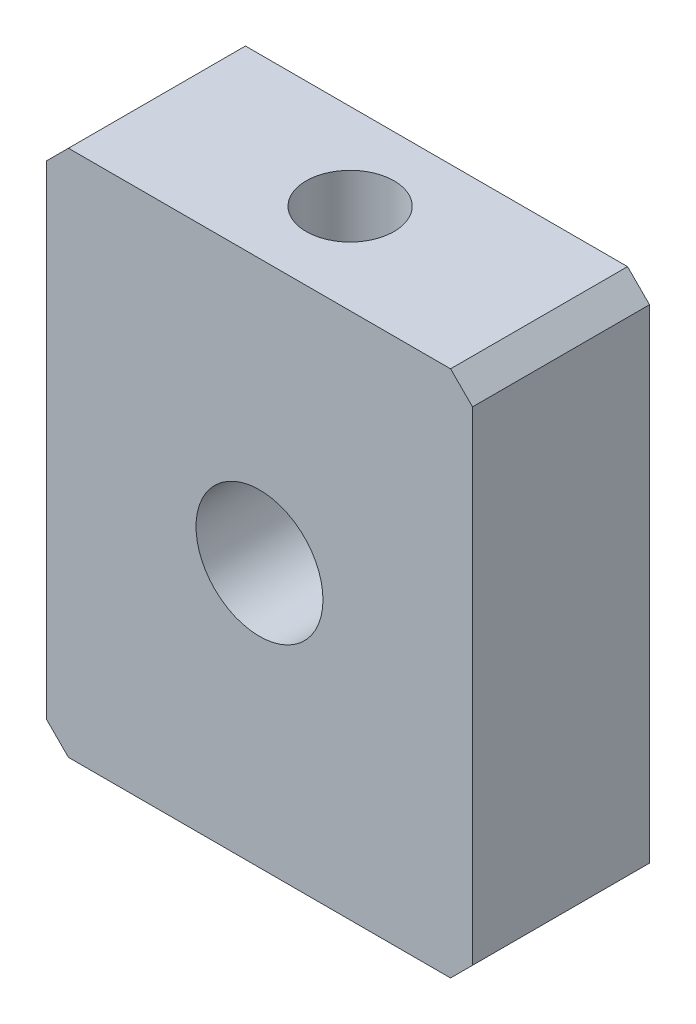
SolidWorks part; units mm, degrees
ref_plane "前视基准面" through (0, 0, 0) normal (0, 0, 1) x (1, 0, 0)
ref_plane "上视基准面" through (0, 0, 0) normal (0, 1, 0) x (1, 0, 0)
ref_plane "右视基准面" through (0, 0, 0) normal (1, 0, 0) x (0, 0, -1)
other "Configuration Table"
sketch "草图1" plane through (0, 0, 52.0651) normal (0, 0, 1) x (1, 0, 0)
  line L0 (-369.3491, 311.962) -> (-369.3491, 664.552) construction
  line L1 (-466.2591, 311.962) -> (-369.3491, 311.962)
  line L2 (-466.2591, 311.962) -> (-466.2591, 431.962)
  line L3 (-466.2591, 431.962) -> (-369.3491, 431.962)
  line L4 (-369.3491, 311.962) -> (-369.3491, 431.962)
  dimension "D1" = 120
extrude "凸台-拉伸1" add sketch "草图1" against normal up to surface (40.26 mm away)
sketch "草图2" plane through (0, 0, 52.0651) normal (0, 0, 1) x (1, 0, 0)
  line L0 (-417.8041, 431.962) -> (-417.8041, 311.962) construction
  line L1 (-369.3491, 431.962) -> (-466.2591, 431.962) construction
  line L2 (-466.2591, 311.962) -> (-369.3491, 311.962) construction
  line L3 (-466.2591, 371.962) -> (-369.3491, 371.962) construction
  line L4 (-466.2591, 431.962) -> (-466.2591, 311.962) construction
  line L5 (-369.3491, 311.962) -> (-369.3491, 431.962) construction
  circle A0 centre (-417.8041, 371.962) radius 10
  circle A1 centre (-494.3388, 524.6403) radius 10
  circle A2 centre (-494.3388, 524.6403) radius 10 construction
extrude "切除-拉伸1" cut sketch "草图2" against normal through all both and the other way through all
sketch "草图3" plane through (0, 431.962, 0) normal (0, 1, 0) x (1, 0, 0)
  circle A0 centre (-417.8041, -31.4551) radius 10
extrude "切除-拉伸2" cut sketch "草图3" against normal blind 20 and the other way through all
chamfer "倒角1" distance 5 angle 45 4 edges at (-466.2591, 311.962, 31.9351) (-369.3491, 311.962, 31.9351) (-369.3491, 431.962, 31.9351) (-466.2591, 431.962, 31.9351)
sketch "草图4" plane through (0, 0, 52.0651) normal (0, 0, 1) x (1, 0, 0)
  circle A0 centre (-417.8041, 371.962) radius 14.4381
extrude "切除-拉伸3" cut sketch "草图4" against normal blind 500
